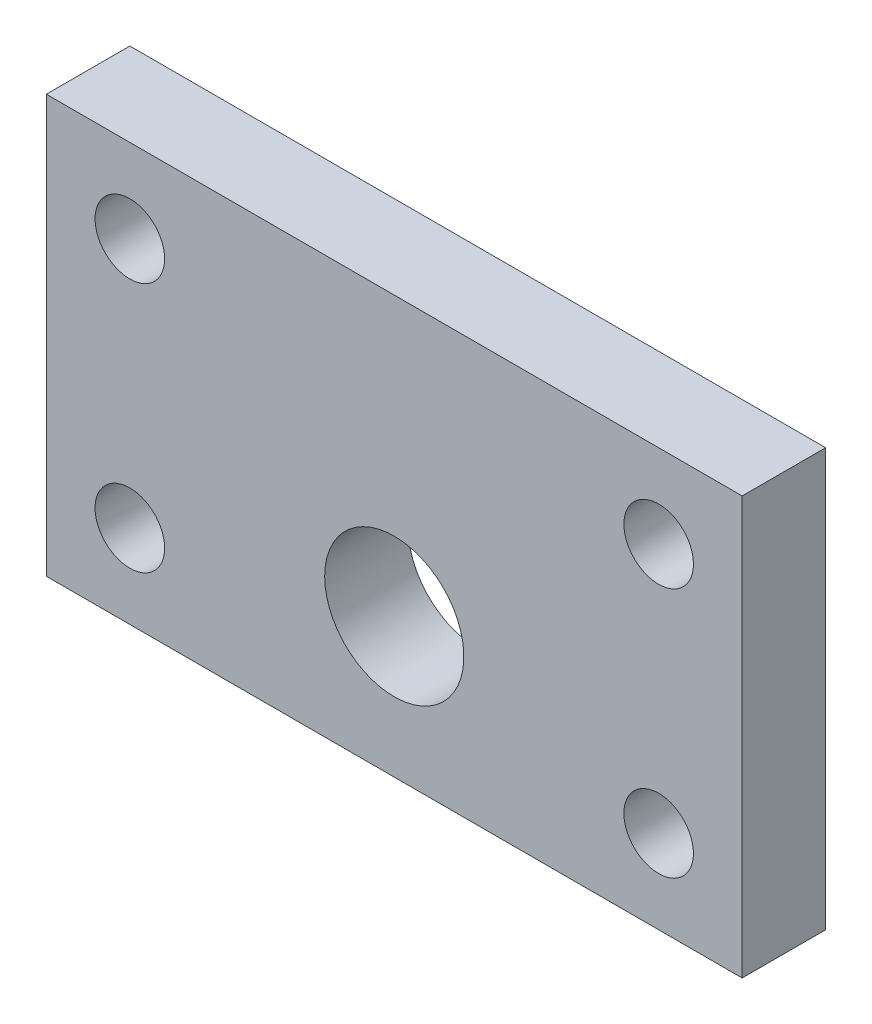
SolidWorks part; units mm, degrees
ref_plane "Front Plane" through (0, 0, 0) normal (0, 0, 1) x (1, 0, 0)
ref_plane "Top Plane" through (0, 0, 0) normal (0, 1, 0) x (1, 0, 0)
ref_plane "Right Plane" through (0, 0, 0) normal (1, 0, 0) x (0, 0, -1)
sketch "Sketch1" plane through (0, 0, 0) normal (0, 0, 1) x (1, 0, 0)
  line L1 (-125, -75) -> (125, -75)
  line L2 (-125, -75) -> (-125, 75)
  line L3 (-125, 75) -> (125, 75)
  line L4 (125, -75) -> (125, 75)
  circle A0 centre (-95, -45) radius 12.5
  circle A1 centre (95, -45) radius 12.5
  circle A2 centre (95, 45) radius 12.5
  circle A3 centre (-95, 45) radius 12.5
  point P0 (0, 0)
  dimension "D5" = 25
  dimension "D1" = 150
  dimension "D2" = 250
  dimension "D3" = 30
  dimension "D4" = 30
  dimension "D6" = 2
  dimension "D7" = 2
extrude "Boss-Extrude1" add sketch "Sketch1" along normal blind 30
sketch "Sketch2" plane through (0, 0, 0) normal (0, 0, -1) x (-1, 0, 0)
  line L0 (125, -75) -> (-125, -75) construction
  line L1 (-125, -75) -> (-125, 75) construction
  circle A0 centre (0, -25) radius 25
  dimension "D2" = 50
  dimension "D1" = 50
  dimension "D3" = 125
extrude "Cut-Extrude1" cut sketch "Sketch2" against normal through all
